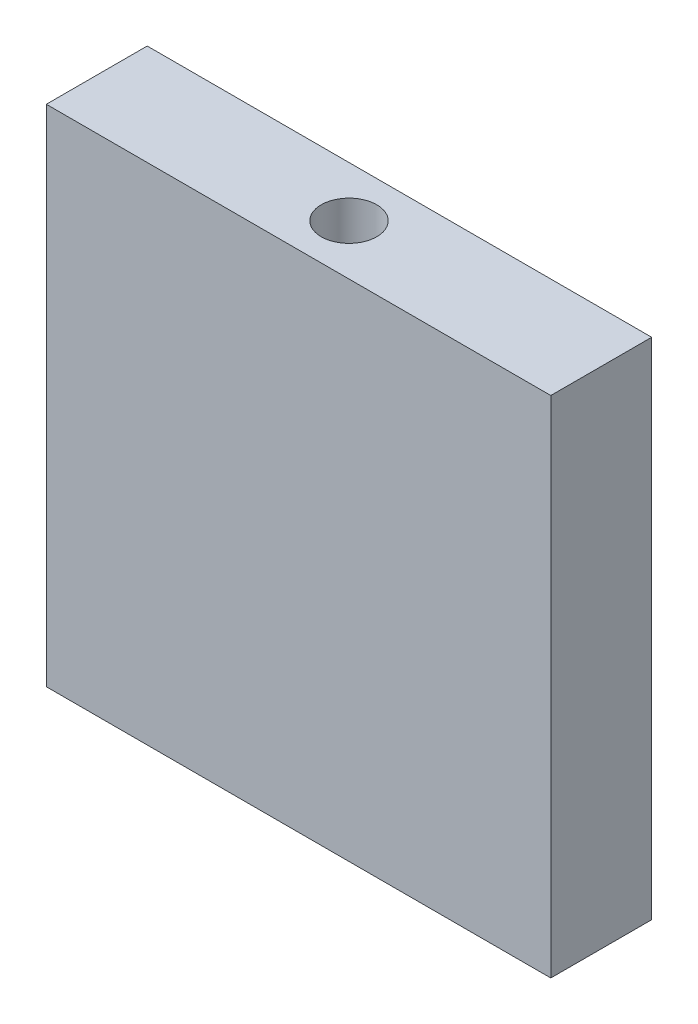
SolidWorks part; units mm, degrees
ref_plane "Front Plane" through (0, 0, 0) normal (0, 0, 1) x (1, 0, 0)
ref_plane "Top Plane" through (0, 0, 0) normal (0, 1, 0) x (1, 0, 0)
ref_plane "Right Plane" through (0, 0, 0) normal (1, 0, 0) x (0, 0, -1)
sketch "Sketch1" plane through (0, 0, 0) normal (0, 0, 1) x (1, 0, 0)
  line L1 (-118.2635, 100) -> (-18.2635, 100)
  line L2 (-118.2635, 100) -> (-118.2635, 0)
  line L3 (-118.2635, 0) -> (-18.2635, 0)
  line L4 (-18.2635, 100) -> (-18.2635, 0)
  dimension "D1" = 100
  dimension "D2" = 100
extrude "Boss-Extrude1" add sketch "Sketch1" along normal blind 20
sketch "Sketch2" plane through (0, 100, 0) normal (0, 1, 0) x (1, 0, 0)
  line L0 (-68.2635, 0) -> (-68.2635, -20) construction
  line L2 (-18.2635, 0) -> (-118.2635, 0) construction
  line L4 (-18.2635, -20) -> (-118.2635, -20) construction
  line L5 (-68.2635, -20) -> (-18.2635, -10) construction
  line L6 (-18.2635, -20) -> (-18.2635, 0) construction
  line L7 (-18.2635, -10) -> (-68.2635, -10) construction
  circle A0 centre (-68.2635, -10) radius 5.5
extrude "Cut-Extrude1" cut sketch "Sketch2" against normal blind 10
